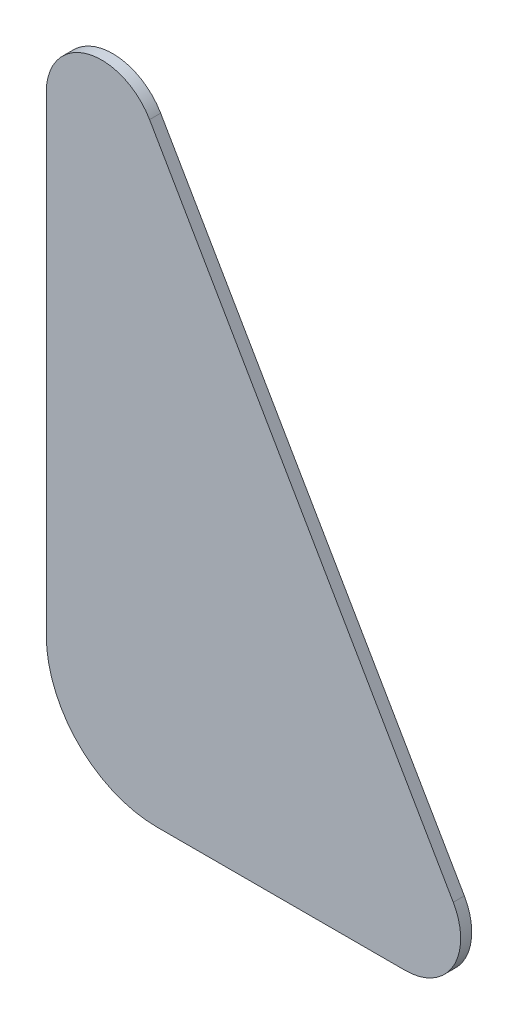
SolidWorks part; units mm, degrees
ref_plane "Front Plane" through (0, 0, 0) normal (0, 0, 1) x (1, 0, 0)
ref_plane "Top Plane" through (0, 0, 0) normal (0, 1, 0) x (1, 0, 0)
ref_plane "Right Plane" through (0, 0, 0) normal (1, 0, 0) x (0, 0, -1)
sketch "Sketch1" plane through (0, 0, 0) normal (0, 0, 1) x (1, 0, 0)
  line L0 (0, 100) -> (0, 525)
  line L1 (93.3013, 550) -> (367.5426, 75)
  line L2 (324.2414, 0) -> (100, 0)
  line L3 (-290.1416, 575) -> (615.7293, 575) construction
  arc A0 (0, 100) -> (100, 0) centre (100, 100) ccw
  arc A1 (0, 525) -> (93.3013, 550) centre (50, 525) cw
  arc A2 (367.5426, 75) -> (324.2414, 0) centre (324.2414, 50) cw
  point P8 (0, 0)
  point P11 (0, 711.6025)
  dimension "D2" = 100
  dimension "D3" = 50
  dimension "D1" = 575
  dimension "D4" = 60
extrude "Boss-Extrude1" add sketch "Sketch1" along normal blind 10
